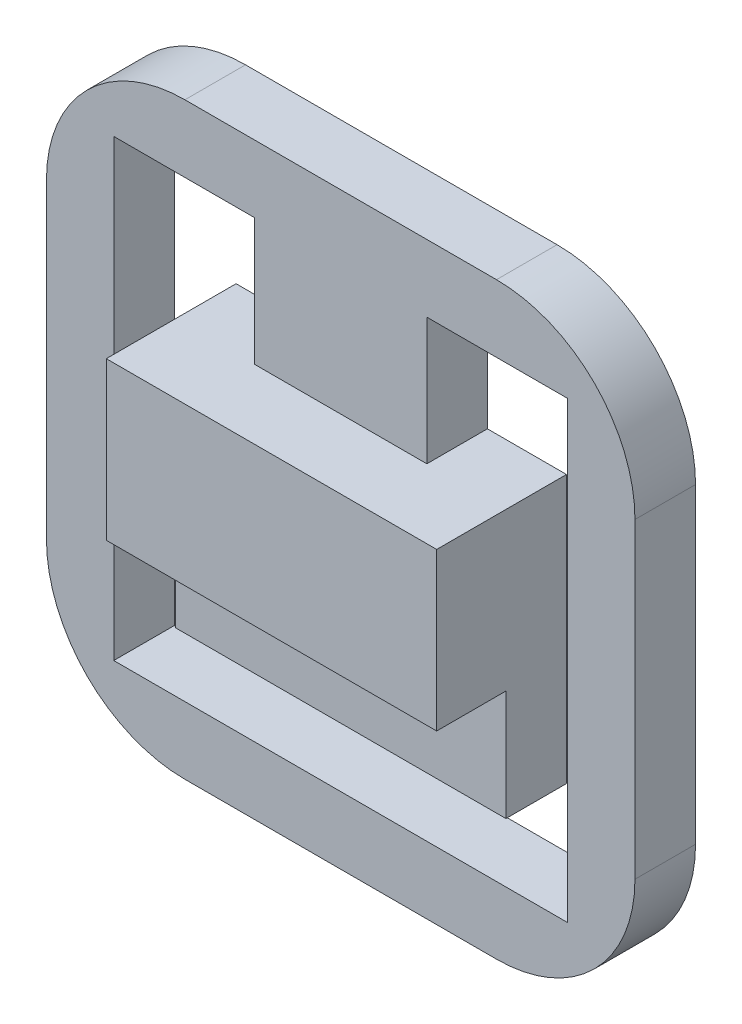
SolidWorks part; units mm, degrees
ref_plane "Front Plane" through (0, 0, 0) normal (0, 0, 1) x (1, 0, 0)
ref_plane "Top Plane" through (0, 0, 0) normal (0, 1, 0) x (1, 0, 0)
ref_plane "Right Plane" through (0, 0, 0) normal (1, 0, 0) x (0, 0, -1)
sketch "Sketch2" plane through (0, 0, 0) normal (0, 0, 1) x (1, 0, 0)
  line L4 (-17, 17) -> (17, 17)
  line L5 (-17, 17) -> (-17, -17)
  line L6 (17, 17) -> (17, -17)
  line L9 (-17, -17) -> (17, -17)
  line L10 (-17, 17) -> (17, -17) construction
  line L11 (17, 17) -> (-17, -17) construction
  line L12 (-13.1124, 13.1124) -> (13.1124, 13.1124)
  line L13 (-13.1124, 13.1124) -> (-13.1124, -13.1124)
  line L14 (13.1124, 13.1124) -> (13.1124, -13.1124)
  line L15 (-13.1124, -13.1124) -> (13.1124, -13.1124)
  line L16 (-13.1124, 13.1124) -> (13.1124, -13.1124) construction
  line L17 (13.1124, 13.1124) -> (-13.1124, -13.1124) construction
  line L18 (-4.9762, 13.1124) -> (-4.9762, 5.775)
  line L19 (-4.9762, 5.775) -> (-9.5441, 5.775)
  line L20 (-9.5441, 5.775) -> (-9.5441, -9.6914)
  line L21 (-9.5441, -9.6914) -> (9.5441, -9.6914)
  line L22 (9.5441, -9.6914) -> (9.5441, 5.775)
  line L23 (9.5441, 5.775) -> (4.9762, 5.775)
  line L24 (4.9762, 5.775) -> (4.9762, 13.1124)
  line L25 (0, 17) -> (0, -17) construction
  point P1 (0, 0)
  point P2 (0, 0)
  dimension "D1" = 34
extrude "Boss-Extrude1" add sketch "Sketch2" along normal blind 3.5 contours L5 L9 L6 L4 L15 L13 L12 L14 | L23 L24 L12 L18 L19 L20 L21 L22
sketch "Sketch4" plane through (0, 0, 3.5) normal (0, 0, 1) x (1, 0, 0)
  line L0 (9.5441, -9.6914) -> (9.5441, 5.775) construction
  line L1 (-9.5441, 5.775) -> (9.5441, 5.775)
  line L2 (-9.5441, 5.775) -> (-9.5441, -3.3108)
  line L3 (-9.5441, -3.3108) -> (9.5441, -3.3108)
  line L4 (9.5441, 5.775) -> (9.5441, -3.3108)
extrude "Boss-Extrude2" add sketch "Sketch4" along normal blind 4
fillet "Fillet1" radius 8 4 edges at (17, -17, 1.75) (-17, -17, 1.75) (-17, 17, 1.75) (17, 17, 1.75)
